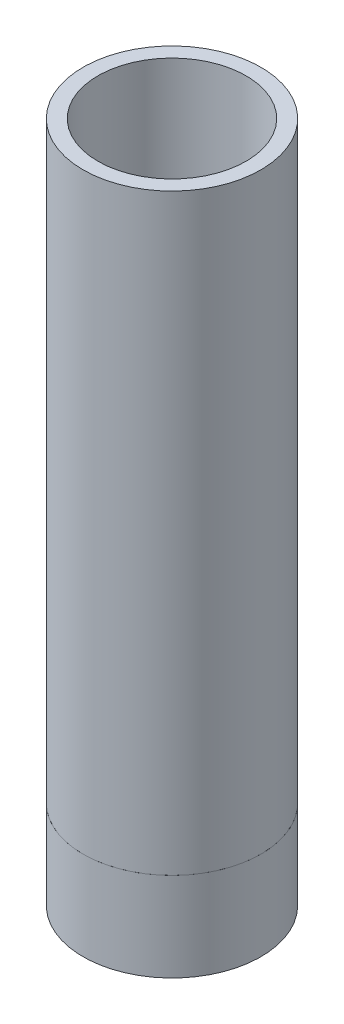
SolidWorks part; units mm, degrees
ref_plane "Front Plane" through (0, 0, 0) normal (0, 0, 1) x (1, 0, 0)
ref_plane "Top Plane" through (0, 0, 0) normal (0, 1, 0) x (1, 0, 0)
ref_plane "Right Plane" through (0, 0, 0) normal (1, 0, 0) x (0, 0, -1)
sketch "Sketch1" plane through (0, 0, 0) normal (0, 1, 0) x (1, 0, 0)
  circle A0 centre (0, 0) radius 12.5
  circle A1 centre (0, 0) radius 15
extrude "Boss-Extrude1" add sketch "Sketch1" along normal blind 100
sketch "Sketch2" plane through (0, 0, 0) normal (0, -1, 0) x (1, 0, 0)
  circle A0 centre (0, 0) radius 12.5
extrude "Boss-Extrude2" add sketch "Sketch2" against normal blind 10 separate body
sketch "Sketch3" plane through (0, 0, 0) normal (0, -1, 0) x (1, 0, 0)
  circle A0 centre (0, 0) radius 12.5
  circle A2 centre (0, 0) radius 15
  dimension "D1" = 25
extrude "Boss-Extrude3" add sketch "Sketch3" along normal blind 15 separate body
sketch "Sketch5" plane through (0, 10, 0) normal (0, 1, 0) x (1, 0, 0)
  line L0 (12.5, 0) -> (8.8, 0) construction
  line L1 (10.65, -1.85) -> (12.3623, -1.85)
  line L2 (10.65, 1.85) -> (12.3805, 1.724)
  arc A0 (12.3805, 1.724) -> (12.5, 0) centre (0, 0) cw
  circle A1 centre (0, 0) radius 12.5 construction
  circle A2 centre (10.65, 0) radius 1.85
  arc A3 (12.3623, -1.85) -> (12.5, 0) centre (0, 0) ccw
  arc A4 (12.5, 0) -> (10.65, -1.85) centre (10.65, 0) cw
  arc A5 (10.65, 1.85) -> (12.5, 0) centre (10.65, 0) cw
  circle M4 centre (0, 0) radius 12.5
  dimension "D1" = 3.7
extrude "Cut-Extrude1" cut sketch "Sketch5" against normal blind 15 contours A2 L1 M4 | A2 L0 | L0 A2 L2 | A2 L2 M4
